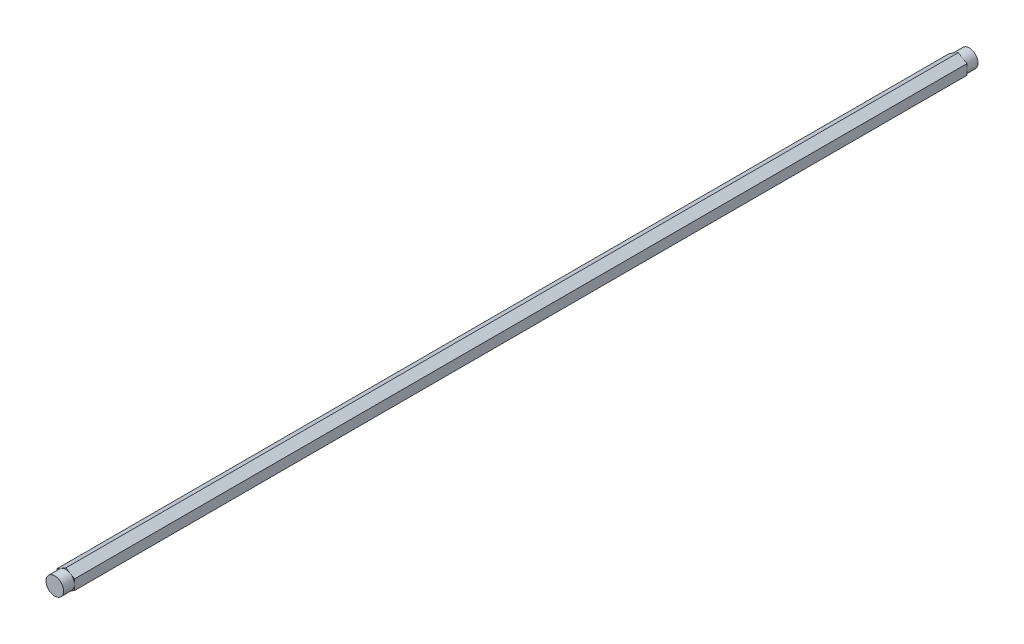
SolidWorks part; units mm, degrees
material "7075-T6 (SN)"
ref_plane "Front Plane" through (0, 0, 0) normal (0, 0, 1) x (1, 0, 0)
ref_plane "Top Plane" through (0, 0, 0) normal (0, 1, 0) x (1, 0, 0)
ref_plane "Right Plane" through (0, 0, 0) normal (1, 0, 0) x (0, 0, -1)
sketch "Sketch1" plane through (0, 0, 0) normal (0, 0, 1) x (1, 0, 0)
  line L1 (0, 7.3323) -> (-6.35, 3.6662)
  line L2 (-6.35, 3.6662) -> (-6.35, -3.6662)
  line L3 (-6.35, -3.6662) -> (0, -7.3323)
  line L4 (0, -7.3323) -> (6.35, -3.6662)
  line L5 (6.35, -3.6662) -> (6.35, 3.6662)
  line L6 (6.35, 3.6662) -> (0, 7.3323)
  circle A0 centre (0, 0) radius 6.35 construction
  dimension "D1" = 12.7
extrude "Boss-Extrude1" add sketch "Sketch1" along normal mid plane 660.4
sketch "Sketch2" plane through (0, 0, -330.2) normal (0, 0, -1) x (-1, 0, 0)
  circle A0 centre (0, 0) radius 6.35
  dimension "D1" = 12.7
extrude "Cut-Extrude-Thin1" cut sketch "Sketch2" against normal blind 7.9375 thin
mirror "Mirror1" about plane through (0, 0, 0) normal (0, 0, 1) of "Cut-Extrude-Thin1"
